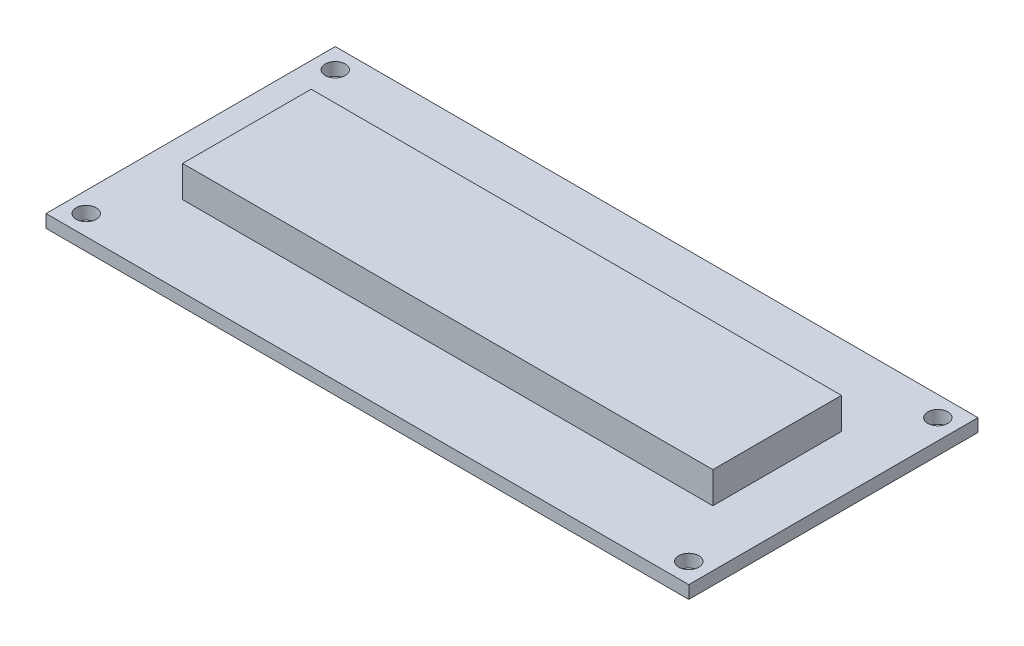
SolidWorks part; units mm, degrees
ref_plane "Front Plane" through (0, 0, 0) normal (0, 0, 1) x (1, 0, 0)
ref_plane "Top Plane" through (0, 0, 0) normal (0, 1, 0) x (1, 0, 0)
ref_plane "Right Plane" through (0, 0, 0) normal (1, 0, 0) x (0, 0, -1)
sketch "Sketch1" plane through (0, 0, 0) normal (0, 1, 0) x (1, 0, 0)
  line L1 (-40, 18) -> (40, 18)
  line L2 (-40, 18) -> (-40, -18)
  line L3 (-40, -18) -> (40, -18)
  line L4 (40, 18) -> (40, -18)
  line L5 (-40, 18) -> (40, -18) construction
  line L6 (-40, -18) -> (40, 18) construction
  point P0 (0, 0)
  dimension "D1" = 80
  dimension "D2" = 36
extrude "Boss-Extrude1" add sketch "Sketch1" along normal blind 1.6
sketch "Sketch3" plane through (0, 1.6, 0) normal (0, 1, 0) x (1, 0, 0)
  line L0 (40, 18) -> (-40, 18) construction
  line L1 (-33, 8) -> (33, 8)
  line L2 (-33, 8) -> (-33, -8)
  line L3 (-33, -8) -> (33, -8)
  line L4 (33, 8) -> (33, -8)
  line L5 (-33, 8) -> (33, -8) construction
  line L6 (-33, -8) -> (33, 8) construction
  line L8 (-40, 18) -> (-40, -18) construction
  point P0 (0, 0)
  dimension "D1" = 10
  dimension "D2" = 7
extrude "Boss-Extrude2" add sketch "Sketch3" along normal blind 3.9
sketch "Sketch4" plane through (0, 1.6, 0) normal (0, 1, 0) x (1, 0, 0)
  line L0 (40, 18) -> (-40, 18) construction
  line L1 (-40, 18) -> (-40, -18) construction
  circle A0 centre (-37.5, 15.5) radius 1.25
  dimension "D1" = 2.5
  dimension "D2" = 2.5
  dimension "D3" = 2.5
extrude "Cut-Extrude1" cut sketch "Sketch4" against normal blind 4.9
ref_plane "Plane1" through (0, 0, 0) normal (-1, 0, 0) x (0, 0, 1)
mirror "Mirror2" about plane through (0, 0, 0) normal (-1, 0, 0) of "Cut-Extrude1"
ref_plane "Plane2" through (0, 0, 0) normal (0, 0, 1) x (1, 0, 0)
mirror "Mirror3" about plane through (0, 0, 0) normal (0, 0, 1) of "Mirror2", "Cut-Extrude1"
